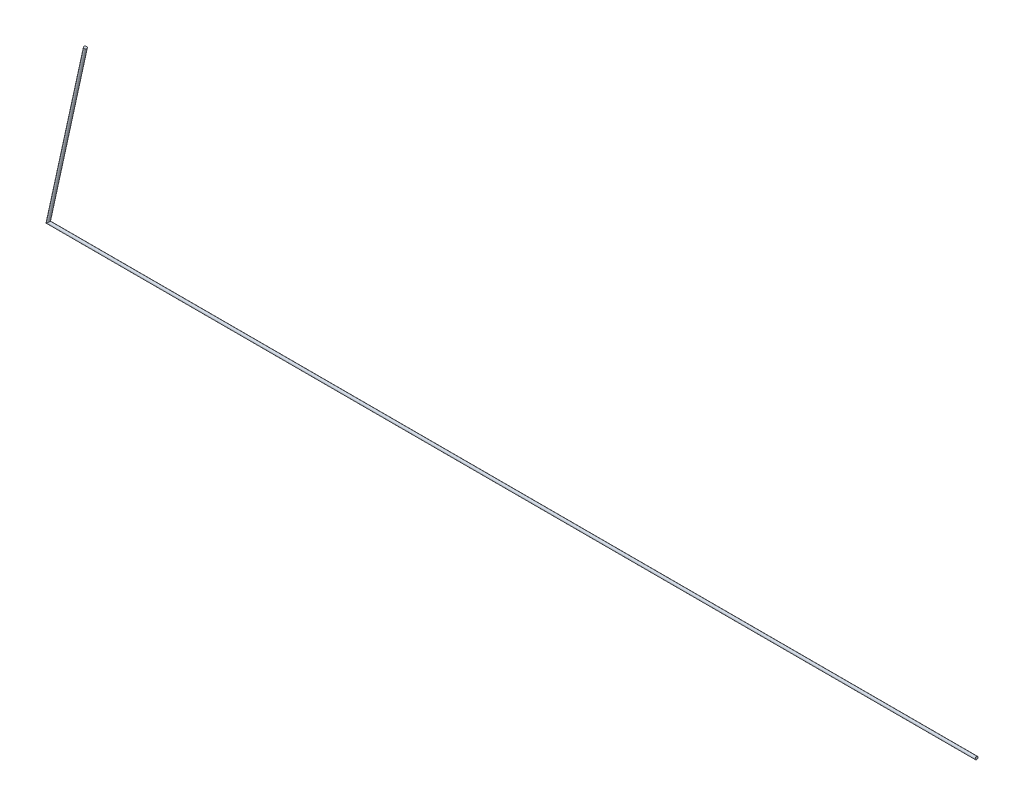
SolidWorks part; units mm, degrees
ref_plane "Front Plane" through (0, 0, 0) normal (0, 0, 1) x (1, 0, 0)
ref_plane "Top Plane" through (0, 0, 0) normal (0, 1, 0) x (1, 0, 0)
ref_plane "Right Plane" through (0, 0, 0) normal (1, 0, 0) x (0, 0, -1)
sketch "Sketch1" plane through (0, 0, 0) normal (0, 0, 1) x (1, 0, 0)
  line L0 (0, 0) -> (-125, 0)
  line L1 (-125, 0) -> (-120, 22.86)
  dimension "D1" = 125
  dimension "D2" = 5
  dimension "0.6``" = 22.86
sketch "Sketch2" plane through (0, 0, 0) normal (1, 0, 0) x (0, 0, -1)
  circle A0 centre (0, 0) radius 0.1905
  dimension "D1" = 0.381
sweep "Sweep1" add profiles "Sketch2" path "Sketch1"
